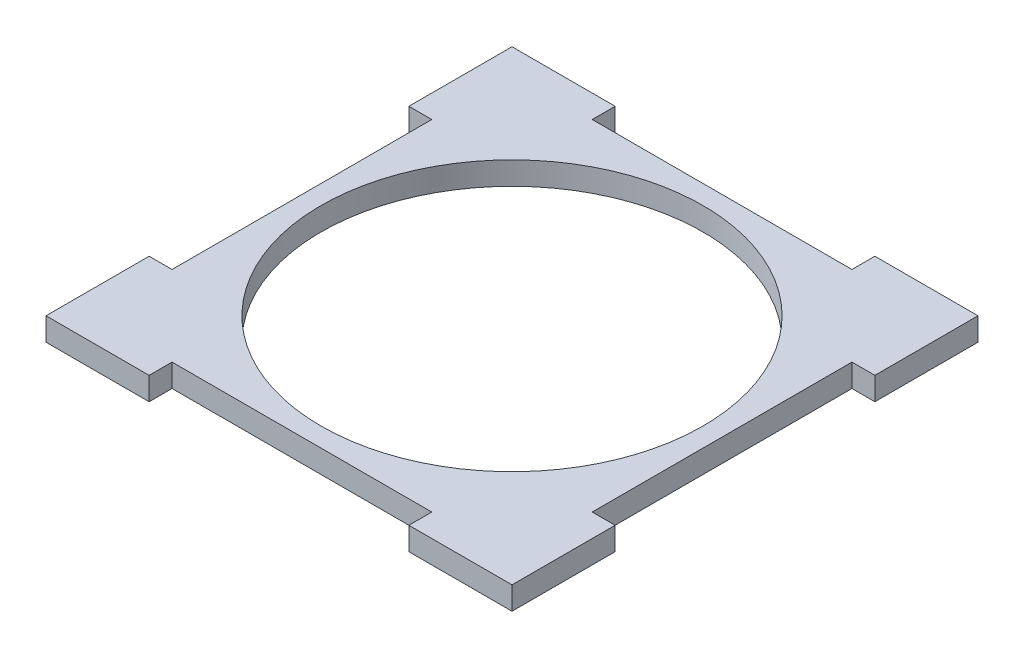
SolidWorks part; units mm, degrees
ref_plane "Alzado" through (0, 0, 0) normal (0, 0, 1) x (1, 0, 0)
ref_plane "Planta" through (0, 0, 0) normal (0, 1, 0) x (1, 0, 0)
ref_plane "Vista lateral" through (0, 0, 0) normal (1, 0, 0) x (0, 0, -1)
sketch "Croquis1" plane through (0, 0, 0) normal (0, 1, 0) x (1, 0, 0)
  line L0 (-27.5, 0) -> (-27.5, 17)
  line L1 (-27.5, 0) -> (-27.5, -17)
  line L2 (-27.5, -17) -> (-30.5, -17)
  line L4 (-30.5, 17) -> (-27.5, 17)
  line L5 (0, 27.5) -> (17, 27.5)
  line L6 (17, 30.5) -> (17, 27.5)
  line L7 (-30.5, 23.75) -> (-30.5, 30.5)
  line L8 (0, 27.5) -> (-17, 27.5)
  line L9 (-17, 27.5) -> (-17, 30.5)
  line L10 (27.5, 0) -> (27.5, -17)
  line L11 (30.5, -17) -> (27.5, -17)
  line L13 (27.5, 0) -> (27.5, 17)
  line L14 (27.5, 17) -> (30.5, 17)
  line L15 (0, -27.5) -> (-17, -27.5)
  line L16 (-17, -30.5) -> (-17, -27.5)
  line L17 (-30.5, 30.5) -> (-23.75, 30.5)
  line L18 (0, -27.5) -> (17, -27.5)
  line L19 (17, -27.5) -> (17, -30.5)
  line L20 (23.75, 30.5) -> (30.5, 30.5)
  line L21 (30.5, 30.5) -> (30.5, 23.75)
  line L24 (23.75, -30.5) -> (30.5, -30.5)
  line L27 (23.75, 30.5) -> (17, 30.5)
  line L28 (30.5, -30.5) -> (30.5, -17)
  line L31 (-23.75, -30.5) -> (-30.5, -30.5)
  line L32 (-23.75, 30.5) -> (-17, 30.5)
  line L33 (-30.5, 17) -> (-30.5, 23.75)
  line L38 (-30.5, -30.5) -> (-30.5, -23.75)
  line L43 (-30.5, -17) -> (-30.5, -23.75)
  line L44 (-23.75, -30.5) -> (-17, -30.5)
  line L45 (23.75, -30.5) -> (17, -30.5)
  line L46 (30.5, 17) -> (30.5, 23.75)
  circle A1 centre (0, 0) radius 25
  point P27 (0, 0)
  dimension "D2" = 50
  dimension "D3" = 17
  dimension "D4" = 17
  dimension "D5" = 3
  dimension "D6" = 4
extrude "Saliente-Extruir1" add sketch "Croquis1" along normal blind 3
